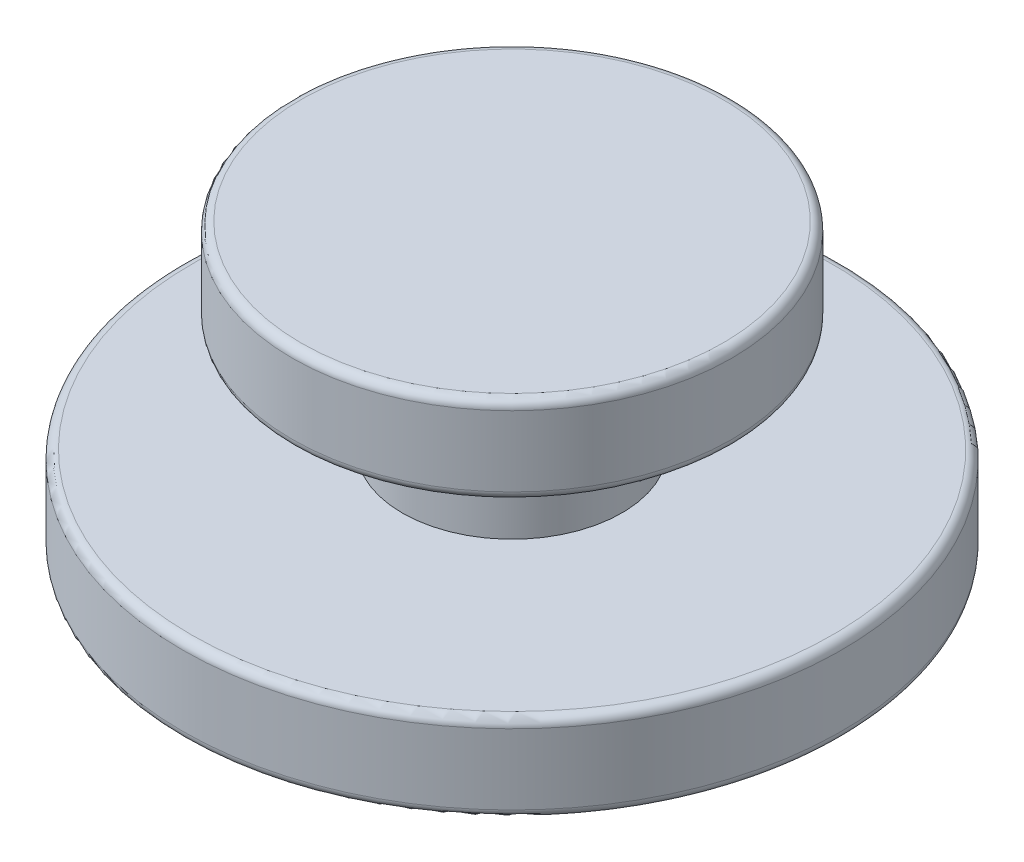
SolidWorks part; units mm, degrees
material "Cast Stainless Steel"
ref_plane "Front Plane" through (0, 0, 0) normal (0, 0, 1) x (1, 0, 0)
ref_plane "Top Plane" through (0, 0, 0) normal (0, 1, 0) x (1, 0, 0)
ref_plane "Right Plane" through (0, 0, 0) normal (1, 0, 0) x (0, 0, -1)
sketch "Sketch1" plane through (0, 0, 0) normal (0, 1, 0) x (1, 0, 0)
  circle A0 centre (0, 0) radius 7.5
  dimension "D1" = 15
extrude "Boss-Extrude1" add sketch "Sketch1" along normal blind 2
sketch "Sketch2" plane through (0, 2, 0) normal (0, 1, 0) x (1, 0, 0)
  circle A0 centre (0, 0) radius 2.5
  dimension "D1" = 5
extrude "Boss-Extrude2" add sketch "Sketch2" along normal blind 2.5
sketch "Sketch3" plane through (0, 4.5, 0) normal (0, 1, 0) x (1, 0, 0)
  circle A0 centre (0, 0) radius 5
  dimension "D1" = 10
extrude "Boss-Extrude3" add sketch "Sketch3" along normal blind 2
fillet "Fillet1" radius 0.2 4 edges at (0, 0, 7.5) (0, 2, 7.5) (0, 4.5, 5) (0, 6.5, 5)
